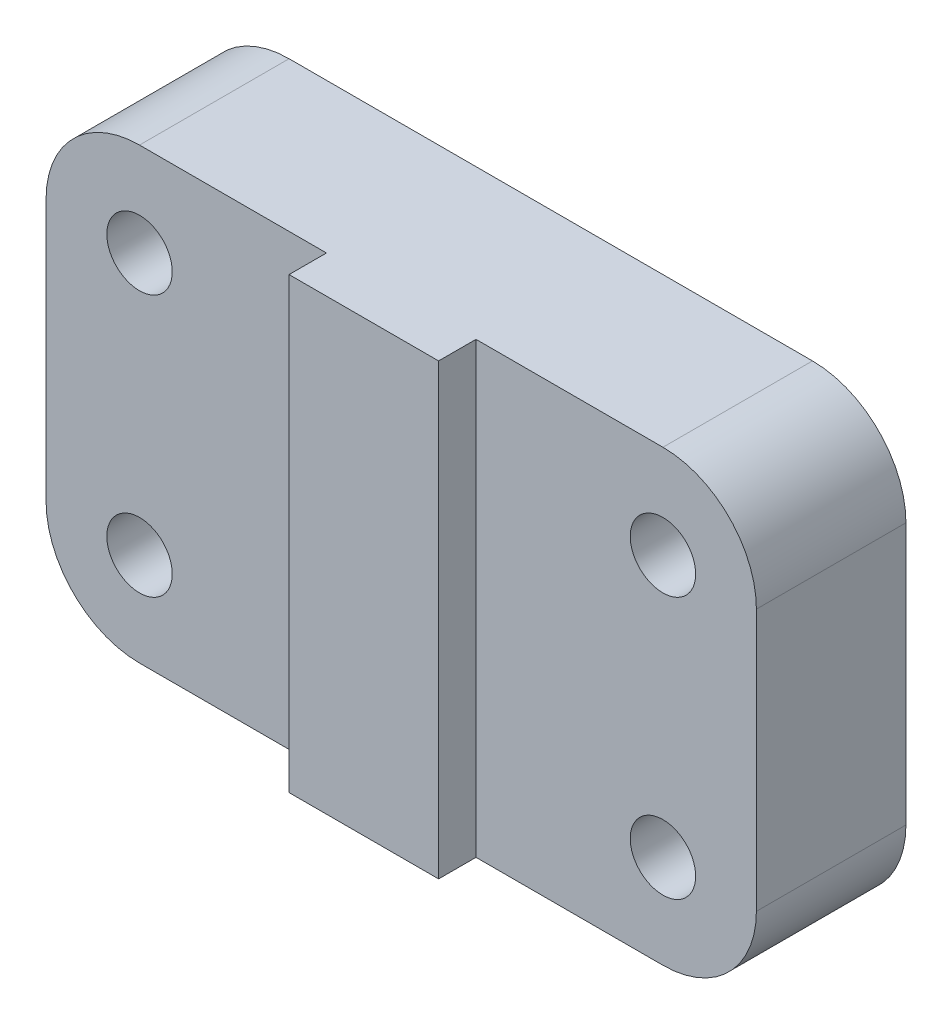
SolidWorks part; units mm, degrees
ref_plane "Front Plane" through (0, 0, 0) normal (0, 0, 1) x (1, 0, 0)
ref_plane "Top Plane" through (0, 0, 0) normal (0, 1, 0) x (1, 0, 0)
ref_plane "Right Plane" through (0, 0, 0) normal (1, 0, 0) x (0, 0, -1)
sketch "Sketch1" plane through (0, 0, 0) normal (0, 0, 1) x (1, 0, 0)
  line L1 (70, 60) -> (-70, 60)
  line L2 (95, 35) -> (95, -35)
  line L3 (70, -60) -> (-70, -60)
  line L4 (-95, 35) -> (-95, -35)
  line L5 (95, 60) -> (-95, -60) construction
  line L6 (95, -60) -> (-95, 60) construction
  arc A0 (-95, -35) -> (-70, -60) centre (-70, -35) ccw
  arc A1 (70, -60) -> (95, -35) centre (70, -35) ccw
  arc A2 (95, 35) -> (70, 60) centre (70, 35) ccw
  arc A3 (-95, 35) -> (-70, 60) centre (-70, 35) cw
  point P0 (0, 0)
  dimension "D3" = 25
  dimension "D1" = 190
  dimension "D2" = 120
extrude "Boss-Extrude3" add sketch "Sketch1" along normal blind 40
sketch "Sketch4" plane through (0, 0, 40) normal (0, 0, 1) x (1, 0, 0)
  point P0 (-70, 35)
  point P1 (-70, -35)
  point P2 (70, -35)
  point P5 (70, 35)
hole_wizard "M20 Tapped Hole1" positions "3DSketch1" profile "Sketch5" tap size "M20" standard "ISO"
sketch3d "3DSketch1"
  point P0 (-70, 35, 40)
  point P3 (-70, -35, 40)
  point P6 (70, -35, 40)
  point P9 (70, 35, 40)
sketch "Sketch5" plane through (-70, 35, 40) normal (1, 0, 0) x (0, -1, 0)
  line L0 (0, 0) -> (0, 30.2575)
  line L1 (0, 30.2575) -> (8.75, 25)
  line L2 (8.75, 25) -> (8.75, 0)
  line L5 (8.75, 0) -> (0, 0)
  line L10 (0, 30.2575) -> (-8.75, 25) construction
  line L11 (0, -6.35) -> (0, 107.95) construction
  dimension "Tap Drill Dia." = 17.5
  dimension "Tap Drill Depth" = 25
  dimension "Drill Angle" = 118
cosmetic thread "Hole Thread1" parameters "D1"=40, "D2"=20
cosmetic thread "Hole Thread2" parameters "D1"=40, "D2"=20
cosmetic thread "Hole Thread3" parameters "D1"=40, "D2"=20
cosmetic thread "Hole Thread4" parameters "D1"=40, "D2"=20
sketch "Sketch6" plane through (0, 0, 40) normal (0, 0, 1) x (1, 0, 0)
  line L0 (70, 60) -> (-70, 60) construction
  line L1 (-20, 60) -> (20, 60)
  line L2 (-20, 60) -> (-20, -60)
  line L3 (-20, -60) -> (20, -60)
  line L4 (20, 60) -> (20, -60)
  line L5 (-70, -60) -> (70, -60) construction
  line L6 (-95, 35) -> (-95, -35) construction
  dimension "D1" = 40
  dimension "D2" = 75
extrude "Boss-Extrude4" add sketch "Sketch6" along normal blind 10
